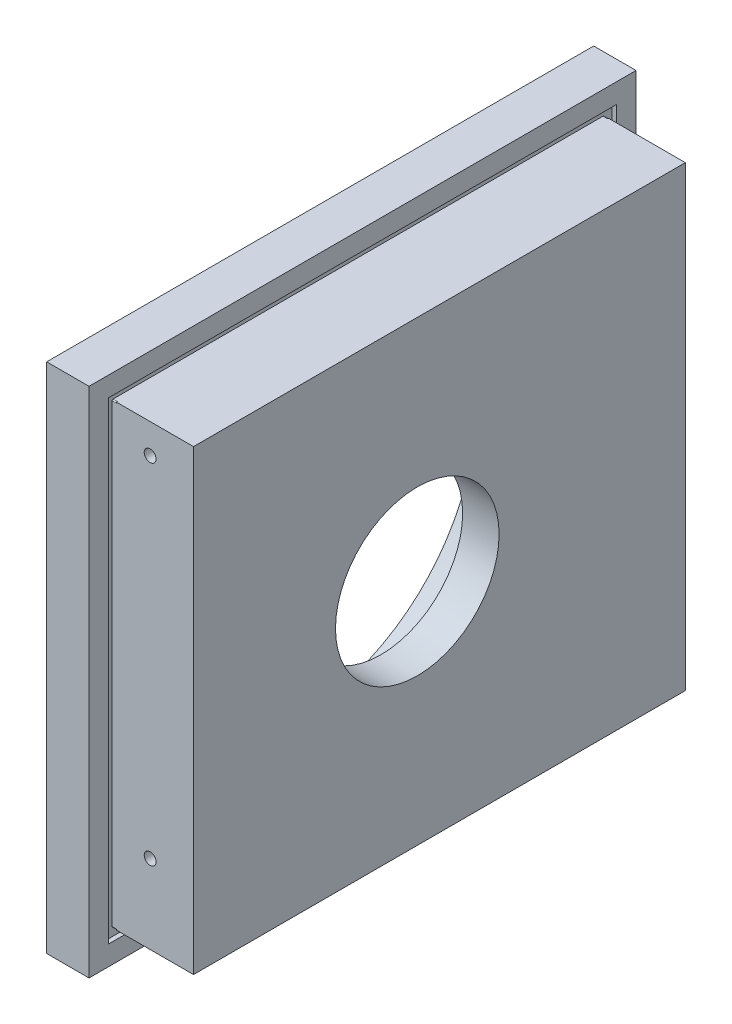
SolidWorks part; units mm, degrees
ref_plane "Front Plane" through (0, 0, 0) normal (0, 0, 1) x (1, 0, 0)
ref_plane "Top Plane" through (0, 0, 0) normal (0, 1, 0) x (1, 0, 0)
ref_plane "Right Plane" through (0, 0, 0) normal (1, 0, 0) x (0, 0, -1)
sketch "Sketch1" plane through (0, 0, 0) normal (1, 0, 0) x (0, 0, -1)
  line L1 (-150, -130) -> (150, -130)
  line L2 (-150, -130) -> (-150, 130)
  line L3 (-150, 130) -> (150, 130)
  line L4 (150, -130) -> (150, 130)
  point P5 (150, 0)
  point P6 (0, -130)
  dimension "D1" = 260
  dimension "D2" = 300
extrude "Boss-Extrude1" add sketch "Sketch1" along normal blind 60.5
sketch "Sketch2" plane through (0, 0, 0) normal (1, 0, 0) x (0, 0, -1)
  line L0 (150, 130) -> (-150, 130) construction
  line L1 (-150, 130) -> (-150, -130) construction
  circle A0 centre (0, 0) radius 90.15
  point P5 (0, 130)
  point P8 (-150, 0)
  dimension "D1" = 180.3
extrude "Cut-Extrude1" cut sketch "Sketch2" along normal blind 42
sketch "Sketch4" plane through (0, 0, 0) normal (1, 0, 0) x (0, 0, -1)
  line L0 (0, 0) -> (0, 107.825) construction
  line L1 (45.5688, 97.7226) -> (0, 0) construction
  line L2 (0, 0) -> (-45.5688, 97.7226) construction
  line L3 (-107.825, 0) -> (107.825, 0) construction
  circle A1 centre (0, 0) radius 125
  circle A8 centre (0, 0) radius 107.825 construction
  circle A9 centre (0, 107.825) radius 5
  circle A10 centre (-82.5987, 69.3086) radius 5
  circle A11 centre (82.5987, 69.3086) radius 5
  circle A12 centre (82.5987, -69.3086) radius 5
  circle A13 centre (0, -107.825) radius 5
  circle A14 centre (-82.5987, -69.3086) radius 5
  dimension "D1" = 250
  dimension "D5" = 10
  dimension "D2" = 215.65
  dimension "D3" = 25
  dimension "D4" = 25
ref_plane "Plane1" through (0, 0, 150) normal (0, 0, 1) x (1, 0, 0)
ref_plane "Plane2" through (0, -130, 0) normal (0, -1, 0) x (-1, 0, 0)
sketch "Sketch9" plane through (0, 0, 0) normal (1, 0, 0) x (0, 0, -1)
  circle A0 centre (0, 0) radius 41.51
  dimension "D1" = 83.02
extrude "Cut-Extrude9" cut sketch "Sketch9" along normal blind 306
ref_plane "Plane3" through (60.5, 0, 0) normal (1, 0, 0) x (0, 0, -1)
ref_plane "Plane5" through (0, 0, -150) normal (0, 0, -1) x (-1, 0, 0)
sketch "Sketch12" plane through (0, 0, 150) normal (0, 0, 1) x (1, 0, 0)
  line L1 (21.5, -130) -> (60.5, -130)
  line L2 (21.5, -130) -> (21.5, 130)
  line L3 (21.5, 130) -> (60.5, 130)
  line L4 (60.5, -130) -> (60.5, 130)
  dimension "D1" = 39
extrude "Cut-Extrude12" cut sketch "Sketch12" against normal blind 36.45
ref_plane "Plane6" through (0, 0, -150) normal (0, 0, -1) x (-1, 0, 0)
sketch "Sketch13" plane through (0, 0, -150) normal (0, 0, -1) x (-1, 0, 0)
  line L1 (-21.5, -130) -> (-60.5, -130)
  line L2 (-21.5, -130) -> (-21.5, 130)
  line L3 (-21.5, 130) -> (-60.5, 130)
  line L4 (-60.5, -130) -> (-60.5, 130)
  dimension "D1" = 39
extrude "Cut-Extrude13" cut sketch "Sketch13" against normal blind 14
sketch "Sketch14" plane through (0, -130, 0) normal (0, -1, 0) x (-1, 0, 0)
  line L5 (-60.5, -113.55) -> (-21.5, -113.55)
  line L6 (-60.5, -113.55) -> (-60.5, 136)
  line L7 (-60.5, 136) -> (-21.5, 136)
  line L8 (-21.5, -113.55) -> (-21.5, 136)
extrude "Cut-Extrude14" cut sketch "Sketch14" against normal blind 14
sketch "Sketch15" plane through (0, 0, 0) normal (1, 0, 0) x (0, 0, -1)
  line L0 (-150, -130) -> (150, -130) construction
  line L1 (-150, 130) -> (-127.55, 130)
  line L2 (-150, 130) -> (-150, -130)
  line L3 (-150, -130) -> (-127.55, -130)
  line L4 (-127.55, 130) -> (-127.55, -130)
  dimension "D1" = 22.45
extrude "Cut-Extrude15" cut sketch "Sketch15" along normal through all
sketch "Sketch16" plane through (0, 0, 150) normal (0, 0, 1) x (1, 0, 0)
  line L0 (21.5, 130) -> (21.5, -116) construction
  line L1 (60.5, 130) -> (21.5, 130) construction
  line L2 (21.5, -130) -> (0, -130) construction
  circle A0 centre (38.5, 101) radius 3
  circle A1 centre (38.5, -76) radius 3
  dimension "D4" = 6
  dimension "D5" = 6
  dimension "D1" = 17
  dimension "D2" = 29
  dimension "D3" = 54
sketch "Sketch17" plane through (0, 0, -150) normal (0, 0, -1) x (-1, 0, 0)
  circle A0 centre (-38.5, 101) radius 3
  circle A1 centre (-38.5, -76) radius 3
  circle A2 centre (-38.5, -76) radius 3 construction
  circle A3 centre (-38.5, 101) radius 3 construction
hole_wizard "Ø6.0mm Dowel Hole1" positions "Sketch18" profile "Sketch19" hole size "Ø6.0" standard "ISO"
sketch "Sketch18" plane through (0, 0, -136) normal (0, 0, -1) x (-1, 0, 0)
  point P0 (-38.5, 101)
  point P3 (-38.5, -76)
sketch "Sketch19" plane through (38.5, 101, -136) normal (1, 0, 0) x (0, 1, 0)
  line L0 (0, 0) -> (0, 31.8026)
  line L1 (0, 31.8026) -> (3, 30)
  line L2 (3, 30) -> (3, 0)
  line L5 (3, 0) -> (0, 0)
  line L10 (0, 31.8026) -> (-3, 30) construction
  line L11 (0, -6.35) -> (0, 107.95) construction
  dimension "Hole Dia." = 6
  dimension "Hole Depth" = 30
  dimension "Drill Angle" = 118
hole_wizard "Ø6.0mm Dowel Hole2" positions "Sketch20" profile "Sketch21" hole size "Ø6.0" standard "ISO"
sketch "Sketch20" plane through (0, 0, 113.55) normal (0, 0, 1) x (1, 0, 0)
  point P0 (38.5, 101)
  point P3 (38.5, -76)
sketch "Sketch21" plane through (38.5, 101, 113.55) normal (1, 0, 0) x (0, -1, 0)
  line L0 (0, 0) -> (0, 31.8026)
  line L1 (0, 31.8026) -> (3, 30)
  line L2 (3, 30) -> (3, 0)
  line L5 (3, 0) -> (0, 0)
  line L10 (0, 31.8026) -> (-3, 30) construction
  line L11 (0, -6.35) -> (0, 107.95) construction
  dimension "Hole Dia." = 6
  dimension "Hole Depth" = 30
  dimension "Drill Angle" = 118
sketch "Sketch22" plane through (0, -130, 0) normal (0, -1, 0) x (-1, 0, 0)
  line L0 (0, -127.55) -> (0, 150) construction
  line L3 (-21.5, -127.55) -> (0, -127.55) construction
  line L4 (-21.5, 150) -> (0, 150) construction
  circle A0 centre (-40, -97.55) radius 3
  circle A1 centre (-40, 120) radius 3
  dimension "D4" = 6
  dimension "D5" = 6
  dimension "D2" = 30
  dimension "D3" = 30
  dimension "D1" = 40
  dimension "D6" = 40
hole_wizard "Ø6.0mm Dowel Hole3" positions "Sketch23" profile "Sketch24" hole size "Ø6.0" standard "ISO"
sketch "Sketch23" plane through (0, -116, 0) normal (0, -1, 0) x (-1, 0, 0)
  point P0 (-40, -97.55)
  point P3 (-40, 120)
sketch "Sketch24" plane through (40, -116, 97.55) normal (1, 0, 0) x (0, 0, -1)
  line L0 (0, 0) -> (0, 16.8026)
  line L1 (0, 16.8026) -> (3, 15)
  line L2 (3, 15) -> (3, 0)
  line L5 (3, 0) -> (0, 0)
  line L10 (0, 16.8026) -> (-3, 15) construction
  line L11 (0, -6.35) -> (0, 107.95) construction
  dimension "Hole Dia." = 6
  dimension "Hole Depth" = 15
  dimension "Drill Angle" = 118
sketch "Sketch25" plane through (0, 0, -150) normal (0, 0, -1) x (-1, 0, 0)
  line L0 (-21.5, -130) -> (-21.5, 130) construction
  line L1 (-60.5, 130) -> (-21.5, 130)
  line L2 (-60.5, 130) -> (-60.5, 116)
  line L3 (-60.5, 116) -> (-21.5, 116)
  line L4 (-21.5, 130) -> (-21.5, 116)
  dimension "D1" = 14
extrude "Cut-Extrude16" cut sketch "Sketch25" against normal through all
ref_plane "Plane7" through (21.5, 0, 0) normal (1, 0, 0) x (0, 0, -1)
sketch "Sketch26" plane through (21.5, 0, 0) normal (1, 0, 0) x (0, 0, -1)
  line L1 (-113.05, 116) -> (135.5, 116)
  line L2 (-113.55, 115.5) -> (-113.55, -115.5)
  line L3 (-113.05, -116) -> (135.5, -116)
  line L4 (136, 115.5) -> (136, -115.5)
  line L5 (-117.55, 120) -> (140, 120)
  line L6 (-117.55, 120) -> (-117.55, -120)
  line L7 (-117.55, -120) -> (140, -120)
  line L8 (140, 120) -> (140, -120)
  arc A0 (-113.55, -115.5) -> (-113.05, -116) centre (-113.05, -115.5) ccw
  arc A1 (135.5, -116) -> (136, -115.5) centre (135.5, -115.5) ccw
  arc A2 (135.5, 116) -> (136, 115.5) centre (135.5, 115.5) cw
  arc A3 (-113.05, 116) -> (-113.55, 115.5) centre (-113.05, 115.5) ccw
  point P14 (136, -116)
  point P19 (-113.55, 116)
  dimension "D5" = 0.5
  dimension "D1" = 4
  dimension "D2" = 4
  dimension "D3" = 4
  dimension "D4" = 4
extrude "Cut-Extrude17" cut sketch "Sketch26" against normal blind 2.3
hole_wizard "Ø10.0mm Dowel Hole1" positions "Sketch29" profile "Sketch30" hole size "Ø10.0" standard "ISO"
sketch "Sketch29" plane through (0, 0, 0) normal (-1, 0, 0) x (0, 0, 1)
  point P0 (-82.5987, 69.3086)
  point P3 (0, 107.825)
  point P6 (82.5987, 69.3086)
  point P9 (82.5987, -69.3086)
  point P12 (0, -107.825)
  point P15 (-82.5987, -69.3086)
sketch "Sketch30" plane through (0, 69.3086, -82.5987) normal (0, 1, 0) x (0, 0, 1)
  line L0 (0, 0) -> (0, 18.0043)
  line L1 (0, 18.0043) -> (5, 15)
  line L2 (5, 15) -> (5, 0)
  line L5 (5, 0) -> (0, 0)
  line L10 (0, 18.0043) -> (-5, 15) construction
  line L11 (0, -6.35) -> (0, 107.95) construction
  dimension "Hole Dia." = 10
  dimension "Hole Depth" = 15
  dimension "Drill Angle" = 118
sketch "Sketch31" plane through (0, 0, 0) normal (1, 0, 0) x (0, 0, -1)
  circle A0 centre (0, 0) radius 95.65
  circle A2 centre (0, 0) radius 91.65
  circle A4 centre (0, 0) radius 90.15 construction
  dimension "D1" = 1.5
  dimension "D2" = 4
extrude "Cut-Extrude18" cut sketch "Sketch31" along normal blind 2.3
sketch "Sketch32" plane through (0, -130, 0) normal (0, -1, 0) x (-1, 0, 0)
  line L2 (0, -127.55) -> (0, 150) construction
  line L5 (-21.5, -127.55) -> (0, -127.55) construction
  circle A0 centre (-9, 9.45) radius 2.25
  dimension "D3" = 4.5
  dimension "D1" = 9
  dimension "D2" = 137
extrude "Cut-Extrude19" cut sketch "Sketch32" against normal blind 68
